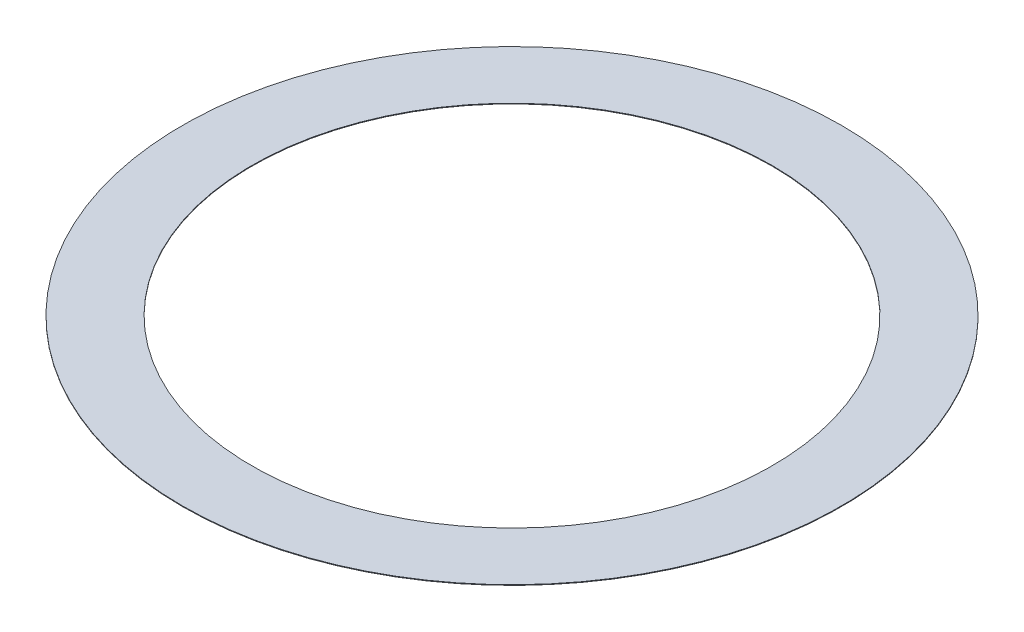
SolidWorks part; units mm, degrees
ref_plane "Front Plane" through (0, 0, 0) normal (0, 0, 1) x (1, 0, 0)
ref_plane "Top Plane" through (0, 0, 0) normal (0, 1, 0) x (1, 0, 0)
ref_plane "Right Plane" through (0, 0, 0) normal (1, 0, 0) x (0, 0, -1)
sketch "Sketch1" plane through (0, 0, 0) normal (0, 1, 0) x (1, 0, 0)
  circle A0 centre (0, 0) radius 16.5
  circle A1 centre (0, 0) radius 20.9
  dimension "D1" = 33
  dimension "D2" = 41.8
extrude "Boss-Extrude1" add sketch "Sketch1" along normal blind 0.04
